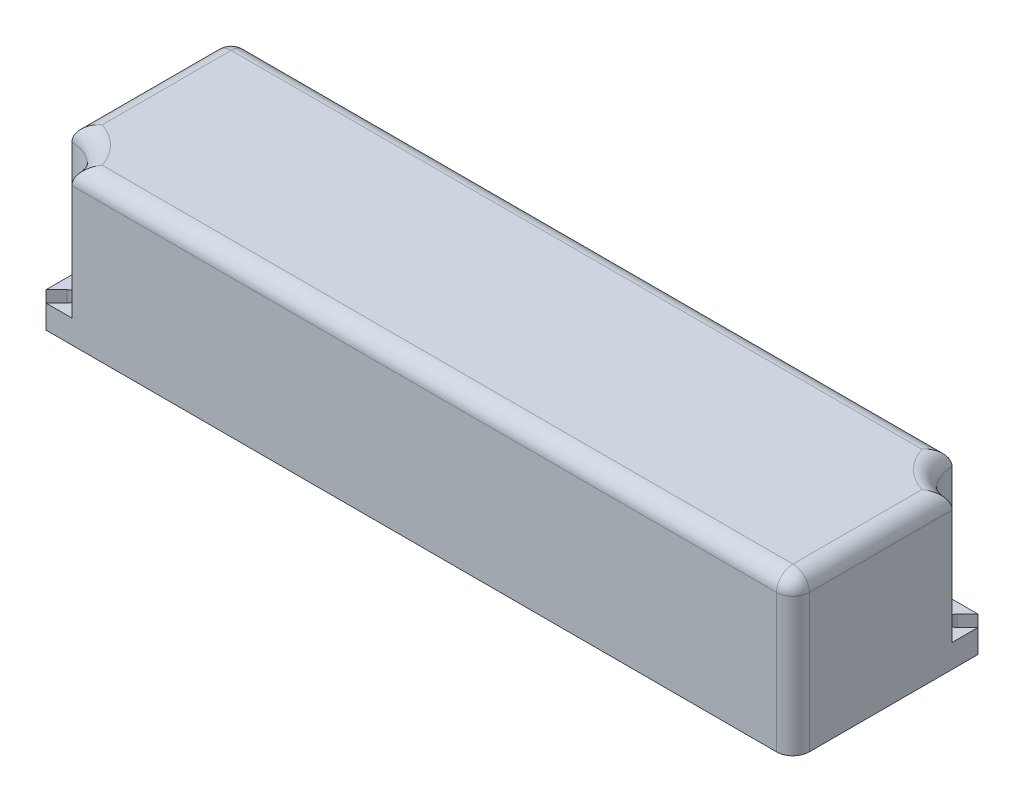
SolidWorks part; units mm, degrees
ref_plane "Ebene vorne" through (0, 0, 0) normal (0, 0, 1) x (1, 0, 0)
ref_plane "Ebene oben" through (0, 0, 0) normal (0, 1, 0) x (1, 0, 0)
ref_plane "Ebene rechts" through (0, 0, 0) normal (1, 0, 0) x (0, 0, -1)
sketch "Skizze1" plane through (0, 0, 0) normal (0, 1, 0) x (1, 0, 0)
  line L1 (81, 21) -> (-81, 21)
  line L2 (81, 21) -> (81, -21)
  line L3 (81, -21) -> (-81, -21)
  line L4 (-81, 21) -> (-81, -21)
  line L5 (81, 21) -> (-81, -21) construction
  line L6 (81, -21) -> (-81, 21) construction
  point P0 (0, 0)
  dimension "D1" = 162
  dimension "D2" = 42
extrude "Aufsatz-Linear austragen1" add sketch "Skizze1" along normal blind 33
sketch "Skizze2" plane through (0, 33, 0) normal (0, 1, 0) x (1, 0, 0)
  circle A0 centre (-81, -21) radius 8
  circle A1 centre (81, 21) radius 8
  dimension "D1" = 16
extrude "Schnitt-Linear austragen1" cut sketch "Skizze2" against normal offset from surface (28 mm away) 5 up to face at (0, 0, 0)
fillet "Verrundung1" radius 3.5 8 edges at (4, 33, 21) (-75.3431, 33, 15.3431) (-81, 33, -4) (-4, 33, -21) (75.3431, 33, -15.3431) (81, 33, 4) (-81, 16.5, -21) (81, 16.5, 21)
sketch "Skizze3" plane through (0, 5, 0) normal (0, 1, 0) x (1, 0, 0)
  line L0 (77.5, 17.5) -> (81, 21) construction
  line L1 (81, 21) -> (77.5, 21) construction
  line L2 (81, 21) -> (81, 17.5) construction
  line L3 (81, 17.5) -> (77.5, 17.5) construction
  line L4 (77.5, 21) -> (77.5, 17.5) construction
  line L5 (81, 21) -> (77.5, 17.5) construction
  line L6 (81, 17.5) -> (77.5, 21) construction
  line L7 (76.2626, 18.7374) -> (79.7626, 22.2374)
  line L8 (78.7374, 16.2626) -> (82.2374, 19.7626)
  line L9 (-77.5, -17.5) -> (-81, -21) construction
  line L10 (-81, -21) -> (-77.5, -21) construction
  line L11 (-81, -21) -> (-81, -17.5) construction
  line L12 (-81, -17.5) -> (-77.5, -17.5) construction
  line L13 (-77.5, -21) -> (-77.5, -17.5) construction
  line L14 (-81, -21) -> (-77.5, -17.5) construction
  line L15 (-81, -17.5) -> (-77.5, -21) construction
  line L16 (-76.2626, -18.7374) -> (-79.7626, -22.2374)
  line L17 (-78.7374, -16.2626) -> (-82.2374, -19.7626)
  arc A0 (-76.2626, -18.7374) -> (-78.7374, -16.2626) centre (-77.5, -17.5) ccw
  arc A1 (76.2626, 18.7374) -> (78.7374, 16.2626) centre (77.5, 17.5) ccw
  arc A2 (82.2374, 19.7626) -> (79.7626, 22.2374) centre (81, 21) ccw
  arc A3 (-82.2374, -19.7626) -> (-79.7626, -22.2374) centre (-81, -21) ccw
  point P4 (79.25, 19.25)
  point P7 (79.25, 19.25)
  point P15 (-79.25, -19.25)
  point P17 (-79.25, -19.25)
  dimension "D2" = 3.5
  dimension "D1" = 3.5
extrude "Schnitt-Linear austragen2" cut sketch "Skizze3" against normal through all
